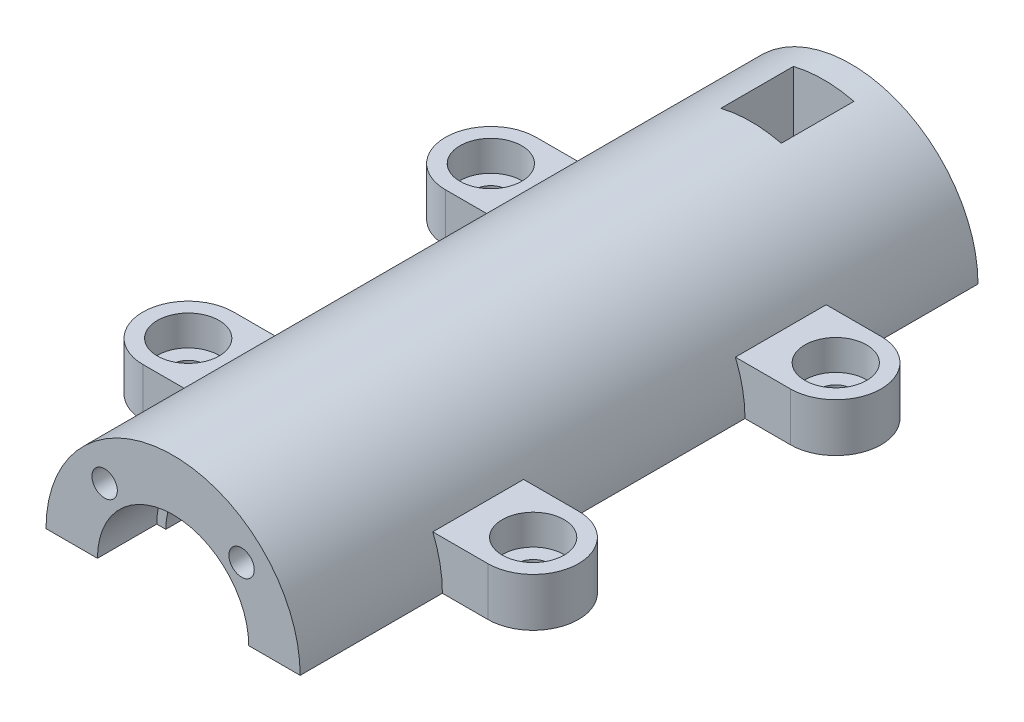
SolidWorks part; units mm, degrees
ref_plane "Спереди" through (0, 0, 0) normal (0, 0, 1) x (1, 0, 0)
ref_plane "Сверху" through (0, 0, 0) normal (0, 1, 0) x (1, 0, 0)
ref_plane "Справа" through (0, 0, 0) normal (1, 0, 0) x (0, 0, -1)
sketch "Эскиз1" plane through (0, 0, 0) normal (0, 1, 0) x (1, 0, 0)
  line L0 (0, 0) -> (21, 0)
  line L1 (0, 0) -> (0, 112)
  line L2 (0, 112) -> (21, 112)
  line L3 (21, 0) -> (21, 112)
  dimension "D1" = 21
  dimension "D2" = 112
revolve "Повернуть1" add sketch "Эскиз1" angle 360 about L1
sketch "Эскиз2" plane through (0, 0, 0) normal (0, 1, 0) x (1, 0, 0)
  line L0 (0, 0) -> (12.5, 0)
  line L1 (12.5, 0) -> (12.5, 9.8)
  line L2 (12.5, 9.8) -> (11, 9.8)
  line L3 (11, 9.8) -> (11, 98.5)
  line L4 (11, 98.5) -> (5, 98.5)
  line L5 (5, 98.5) -> (5, 107.5)
  line L6 (5, 107.5) -> (11, 107.5)
  line L7 (11, 107.5) -> (11, 112)
  line L8 (11, 112) -> (0, 112)
  line L9 (0, 112) -> (0, 0)
  line L10 (21, 112) -> (-21, 112) construction
  dimension "D1" = 12.5
  dimension "D2" = 9.8
  dimension "D3" = 9
  dimension "D4" = 88.7
  dimension "D5" = 11
  dimension "D6" = 11
  dimension "D7" = 5
revolve "Вырез-Повернуть1" cut sketch "Эскиз2" angle 360 about L9
sketch "Эскиз3" plane through (0, 0, 0) normal (0, 0, 1) x (1, 0, 0)
  line L1 (-21, 0) -> (21, 0)
  line L2 (-21, 0) -> (-21, -25)
  line L3 (-21, -25) -> (21, -25)
  line L4 (21, 0) -> (21, -25)
  circle A0 centre (0, 0) radius 21 construction
  dimension "D1" = 25
extrude "Вырез-Вытянуть1" cut sketch "Эскиз3" against normal up to surface (112 mm away) up to face at (-11, 0, -112)
ref_plane "Плоскость1" through (21, 0, 0) normal (1, 0, 0) x (0, 0, -1)
sketch "Эскиз4" plane through (21, 0, 0) normal (1, 0, 0) x (0, 0, -1)
  line L0 (112, 0) -> (0, 0) construction
  line L1 (23.5, 0) -> (38.5, 0)
  line L2 (23.5, 0) -> (23.5, 8)
  line L3 (23.5, 8) -> (38.5, 8)
  line L4 (38.5, 0) -> (38.5, 8)
  point P6 (31, 0)
  dimension "D1" = 15
  dimension "D2" = 8
  dimension "D3" = 31
extrude "Бобышка-Вытянуть1" add sketch "Эскиз4" along normal blind 15 and the other way up to body separate body
sketch "Эскиз5" plane through (0, 8, 0) normal (0, 1, 0) x (1, 0, 0)
  line L0 (36, 38.5) -> (36, 23.5) construction
  line L1 (19.4165, 38.5) -> (36, 38.5) construction
  line L3 (28.5, 38.5) -> (43.5, 38.5)
  line L4 (43.5, 38.5) -> (43.5, 23.5)
  line L5 (43.5, 23.5) -> (28.5, 23.5)
  arc A0 (28.5, 23.5) -> (28.5, 38.5) centre (28.5, 31) ccw
  dimension "D1" = 15
  dimension "D2" = 15
extrude "Вырез-Вытянуть2" cut sketch "Эскиз5" against normal up to surface (8 mm away) up to face at (16.7857, 0, -55.6857)
sketch "Эскиз6" plane through (0, 8, 0) normal (0, 1, 0) x (1, 0, 0)
  circle A0 centre (28.5, 31) radius 2.6
  dimension "D1" = 5.2
extrude "Вырез-Вытянуть3" cut sketch "Эскиз6" against normal up to surface (8 mm away) contours A0 up to face at (16.25, 0, -55.6857)
sketch "Эскиз7" plane through (0, 8, 0) normal (0, 1, 0) x (1, 0, 0)
  circle A0 centre (28.5, 31) radius 5.1
  dimension "D1" = 10.2
extrude "Вырез-Вытянуть4" cut sketch "Эскиз7" against normal blind 5
pattern_linear "Линейный массив1" count 2 spacing 50 along (0, 0, -1) of "Бобышка-Вытянуть1", "Вырез-Вытянуть2", "Вырез-Вытянуть3", "Вырез-Вытянуть4"
mirror "Зеркальное отражение1" about plane through (0, 0, 0) normal (1, 0, 0) of "Линейный массив1", "Бобышка-Вытянуть1", "Вырез-Вытянуть2", "Вырез-Вытянуть3", "Вырез-Вытянуть4"
hole_wizard "Сверление под метчик M51" positions "Трехмерный эскиз2" profile "Эскиз8" hole size "M5" standard "ISO"
sketch3d "Трехмерный эскиз2"
  line L0 (0, 0, 0) -> (0, 21, 0) construction
  arc A0 (21, 0, 0) -> (-21, 0, 0) centre (0, 0, 0) ccw construction
  point P0 (11.3137, 11.3137, 0)
  point P9 (0, 0, 21)
  dimension "D1" = 16
  dimension "D2" = 45
sketch "Эскиз8" plane through (11.3137, 11.3137, 0) normal (1, 0, 0) x (0, -1, 0)
  line L0 (0, 0) -> (0, 26.2618)
  line L1 (0, 26.2618) -> (2.1, 25)
  line L2 (2.1, 25) -> (2.1, 0)
  line L5 (2.1, 0) -> (0, 0)
  line L10 (0, 26.2618) -> (-2.1, 25) construction
  line L11 (0, -6.35) -> (0, 107.95) construction
  dimension "Диаметр отверстия" = 4.2
  dimension "Глубина отверстия" = 25
  dimension "Угол заточки сверла" = 118
cosmetic thread "Условное изображение резьбы1" parameters "D2"=5
pattern_circular "Круговой массив1" count 2 every 90 about axis through (0, 0, 0) along (0, 0, -1) of "Сверление под метчик M51"
ref_plane "Плоскость2" through (0, 0, -56) normal (0, 0, 1) x (1, 0, 0)
mirror "Зеркальное отражение2" about plane through (0, 0, -56) normal (0, 0, 1) of "Круговой массив1", "Сверление под метчик M51"
sketch "Эскиз9" plane through (0, 0, 0) normal (0, 1, 0) x (1, 0, 0)
  line L1 (-5, 107.5) -> (5, 107.5)
  line L2 (-5, 107.5) -> (-5, 95.5)
  line L3 (-5, 95.5) -> (5, 95.5)
  line L4 (5, 107.5) -> (5, 95.5)
  dimension "D1" = 12
  dimension "D2" = 10
extrude "Вырез-Вытянуть6" cut sketch "Эскиз9" along normal up to surface (20.3961 mm away) contours L3 L4 L1 L2
